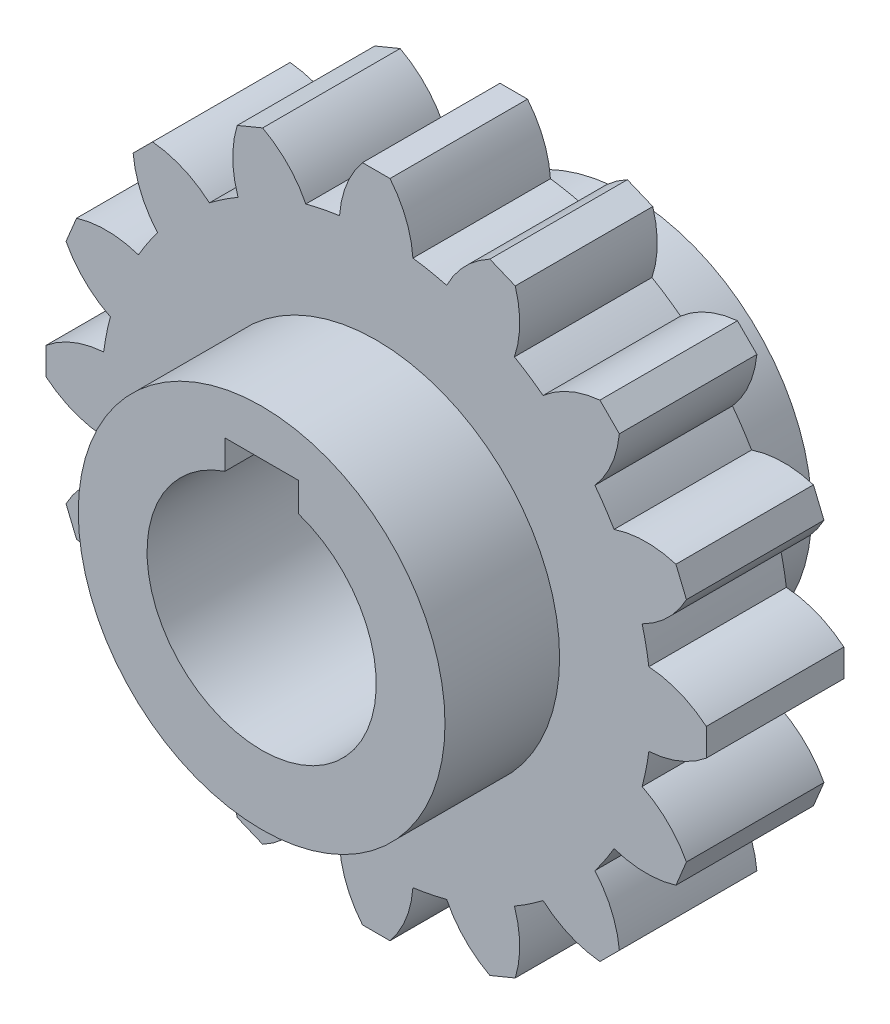
SolidWorks part; units mm, degrees
material "Cast Carbon Steel"
ref_plane "Front Plane" through (0, 0, 0) normal (0, 0, 1) x (1, 0, 0)
ref_plane "Top Plane" through (0, 0, 0) normal (0, 1, 0) x (1, 0, 0)
ref_plane "Right Plane" through (0, 0, 0) normal (1, 0, 0) x (0, 0, -1)
sketch "Sketch1" plane through (0, 0, 0) normal (0, 0, 1) x (1, 0, 0)
  line L0 (0, -40.6806) -> (0, -36) construction
  line L1 (-1.5, 36) -> (1.5, 36)
  line L2 (12.3908, 33.8337) -> (15.1624, 32.6856)
  line L3 (24.3952, 26.5165) -> (26.5165, 24.3952)
  line L4 (32.6856, 15.1624) -> (33.8337, 12.3908)
  line L5 (36, 1.5) -> (36, -1.5)
  line L6 (33.8337, -12.3908) -> (32.6856, -15.1624)
  line L7 (26.5165, -24.3952) -> (24.3952, -26.5165)
  line L8 (15.1624, -32.6856) -> (12.3908, -33.8337)
  line L9 (1.5, -36) -> (-1.5, -36)
  line L10 (-12.3908, -33.8337) -> (-15.1624, -32.6856)
  line L11 (-24.3952, -26.5165) -> (-26.5165, -24.3952)
  line L12 (-32.6856, -15.1624) -> (-33.8337, -12.3908)
  line L13 (-36, -1.5) -> (-36, 1.5)
  line L14 (-33.8337, 12.3908) -> (-32.6856, 15.1624)
  line L15 (-26.5165, 24.3952) -> (-24.3952, 26.5165)
  line L16 (-15.1624, 32.6856) -> (-12.3908, 33.8337)
  line L17 (0, -30) -> (0, 44.2599) construction
  arc A0 (-4, 29.7321) -> (-7.6825, 28.9996) centre (0, 0) ccw
  arc A1 (1.5, 36) -> (4, 29.7321) centre (-6.9748, 28.9873) cw
  arc A2 (-1.5, 36) -> (-4, 29.7321) centre (6.9748, 28.9873) ccw
  arc A3 (12.3908, 33.8337) -> (7.6825, 28.9996) centre (17.5368, 24.1116) ccw
  arc A4 (15.1624, 32.6856) -> (15.0735, 25.9382) centre (4.6491, 29.4499) cw
  arc A5 (24.3952, 26.5165) -> (18.1954, 23.8522) centre (25.429, 15.5652) ccw
  arc A6 (26.5165, 24.3952) -> (23.8522, 18.1954) centre (15.5652, 25.429) cw
  arc A7 (32.6856, 15.1624) -> (25.9382, 15.0735) centre (29.4499, 4.6491) ccw
  arc A8 (33.8337, 12.3908) -> (28.9996, 7.6825) centre (24.1116, 17.5368) cw
  arc A9 (36, 1.5) -> (29.7321, 4) centre (28.9873, -6.9748) ccw
  arc A10 (36, -1.5) -> (29.7321, -4) centre (28.9873, 6.9748) cw
  arc A11 (33.8337, -12.3908) -> (28.9996, -7.6825) centre (24.1116, -17.5368) ccw
  arc A12 (32.6856, -15.1624) -> (25.9382, -15.0735) centre (29.4499, -4.6491) cw
  arc A13 (26.5165, -24.3952) -> (23.8522, -18.1954) centre (15.5652, -25.429) ccw
  arc A14 (24.3952, -26.5165) -> (18.1954, -23.8522) centre (25.429, -15.5652) cw
  arc A15 (15.1624, -32.6856) -> (15.0735, -25.9382) centre (4.6491, -29.4499) ccw
  arc A16 (12.3908, -33.8337) -> (7.6825, -28.9996) centre (17.5368, -24.1116) cw
  arc A17 (1.5, -36) -> (4, -29.7321) centre (-6.9748, -28.9873) ccw
  arc A18 (-1.5, -36) -> (-4, -29.7321) centre (6.9748, -28.9873) cw
  arc A19 (-12.3908, -33.8337) -> (-7.6825, -28.9996) centre (-17.5368, -24.1116) ccw
  arc A20 (-15.1624, -32.6856) -> (-15.0735, -25.9382) centre (-4.6491, -29.4499) cw
  arc A21 (-24.3952, -26.5165) -> (-18.1954, -23.8522) centre (-25.429, -15.5652) ccw
  arc A22 (-26.5165, -24.3952) -> (-23.8522, -18.1954) centre (-15.5652, -25.429) cw
  arc A23 (-32.6856, -15.1624) -> (-25.9382, -15.0735) centre (-29.4499, -4.6491) ccw
  arc A24 (-33.8337, -12.3908) -> (-28.9996, -7.6825) centre (-24.1116, -17.5368) cw
  arc A25 (-36, -1.5) -> (-29.7321, -4) centre (-28.9873, 6.9748) ccw
  arc A26 (-36, 1.5) -> (-29.7321, 4) centre (-28.9873, -6.9748) cw
  arc A27 (-33.8337, 12.3908) -> (-28.9996, 7.6825) centre (-24.1116, 17.5368) ccw
  arc A28 (-32.6856, 15.1624) -> (-25.9382, 15.0735) centre (-29.4499, 4.6491) cw
  arc A29 (-26.5165, 24.3952) -> (-23.8522, 18.1954) centre (-15.5652, 25.429) ccw
  arc A30 (-24.3952, 26.5165) -> (-18.1954, 23.8522) centre (-25.429, 15.5652) cw
  arc A31 (-15.1624, 32.6856) -> (-15.0735, 25.9382) centre (-4.6491, 29.4499) ccw
  arc A32 (-12.3908, 33.8337) -> (-7.6825, 28.9996) centre (-17.5368, 24.1116) cw
  arc A33 (-15.0735, 25.9382) -> (-18.1954, 23.8522) centre (0, 0) ccw
  arc A34 (-23.8522, 18.1954) -> (-25.9382, 15.0735) centre (0, 0) ccw
  arc A35 (-28.9996, 7.6825) -> (-29.7321, 4) centre (0, 0) ccw
  arc A36 (-29.7321, -4) -> (-28.9996, -7.6825) centre (0, 0) ccw
  arc A37 (-25.9382, -15.0735) -> (-23.8522, -18.1954) centre (0, 0) ccw
  arc A38 (-18.1954, -23.8522) -> (-15.0735, -25.9382) centre (0, 0) ccw
  arc A39 (-7.6825, -28.9996) -> (-4, -29.7321) centre (0, 0) ccw
  arc A40 (4, -29.7321) -> (7.6825, -28.9996) centre (0, 0) ccw
  arc A41 (15.0735, -25.9382) -> (18.1954, -23.8522) centre (0, 0) ccw
  arc A42 (23.8522, -18.1954) -> (25.9382, -15.0735) centre (0, 0) ccw
  arc A43 (28.9996, -7.6825) -> (29.7321, -4) centre (0, 0) ccw
  arc A44 (29.7321, 4) -> (28.9996, 7.6825) centre (0, 0) ccw
  arc A45 (25.9382, 15.0735) -> (23.8522, 18.1954) centre (0, 0) ccw
  arc A46 (18.1954, 23.8522) -> (15.0735, 25.9382) centre (0, 0) ccw
  arc A47 (7.6825, 28.9996) -> (4, 29.7321) centre (0, 0) ccw
  dimension "D1" = 60
  dimension "D3" = 11
  dimension "D2" = 6
  dimension "D4" = 8
  dimension "D5" = 3
  dimension "D6" = 16
extrude "Boss-Extrude1" add sketch "Sketch1" along normal mid plane 15
sketch "Sketch2" plane through (0, 0, 0) normal (0, 0, 1) x (1, 0, 0)
  circle A0 centre (0, 0) radius 20
  dimension "D1" = 40
extrude "Boss-Extrude2" add sketch "Sketch2" along normal mid plane 40
sketch "Sketch3" plane through (0, 0, 20) normal (0, 0, 1) x (1, 0, 0)
  line L0 (0, 16.2332) -> (0, 12.5) construction
  line L1 (-4, 15) -> (-4, 11.8427)
  line L2 (-4, 15) -> (4, 15)
  line L3 (4, 15) -> (4, 11.8427)
  arc A0 (-4, 11.8427) -> (4, 11.8427) centre (0, 0) ccw
  dimension "D1" = 15
  dimension "D2" = 25
  dimension "D3" = 8
extrude "Cut-Extrude1" cut sketch "Sketch3" against normal through all both and the other way through all
